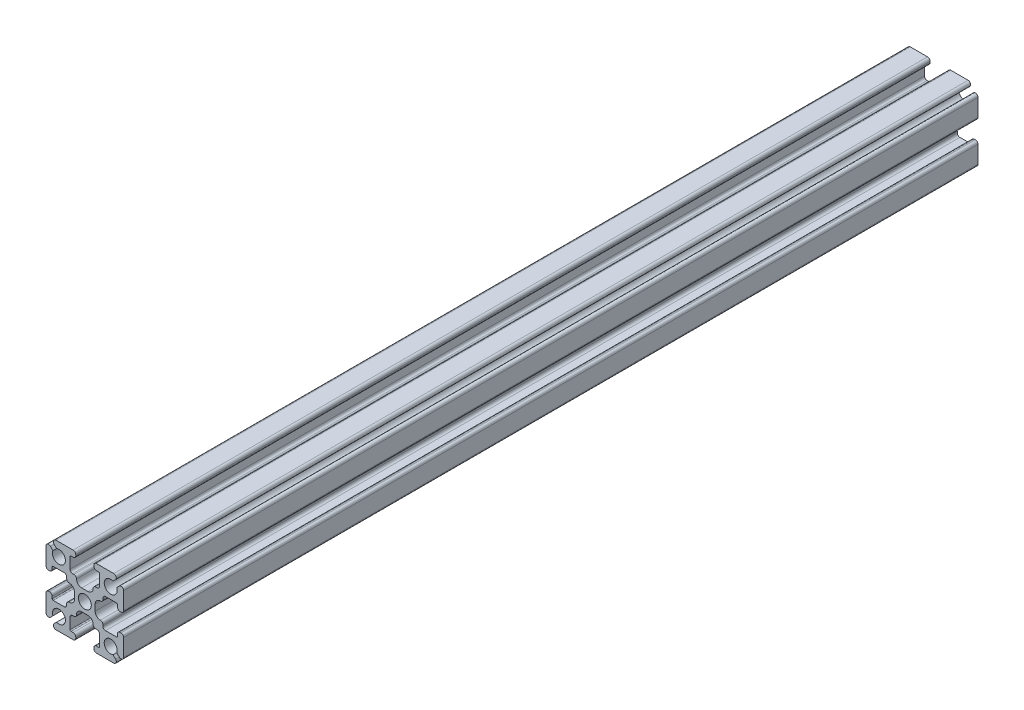
SolidWorks part; units mm, degrees
ref_plane "Front Plane" through (0, 0, 0) normal (0, 0, 1) x (1, 0, 0)
ref_plane "Top Plane" through (0, 0, 0) normal (0, 1, 0) x (1, 0, 0)
ref_plane "Right Plane" through (0, 0, 0) normal (1, 0, 0) x (0, 0, -1)
sketch "Sketch1" plane through (0, 0, 0) normal (0, 0, 1) x (1, 0, 0)
  line L0 (6.6464, 5.9393) -> (6.1636, 5.4565)
  line L1 (5.4565, 6.1636) -> (5.9393, 6.6464)
  line L2 (5.5858, 7.5) -> (2.25, 7.5)
  line L3 (1.75, 7) -> (1.75, 6.8)
  line L4 (2.25, 6.3) -> (2.65, 6.3)
  line L5 (2.85, 6.1) -> (2.85, 4)
  line L6 (2.35, 3.5) -> (2.1, 3.5)
  line L7 (0.6, 2) -> (-0.6, 2)
  line L8 (-2.1, 3.5) -> (-2.35, 3.5)
  line L9 (-2.85, 4) -> (-2.85, 6.1)
  line L10 (-2.65, 6.3) -> (-2.25, 6.3)
  line L11 (-1.75, 6.8) -> (-1.75, 7)
  line L12 (-2.25, 7.5) -> (-5.5858, 7.5)
  line L13 (-5.9393, 6.6464) -> (-5.4565, 6.1636)
  line L14 (-6.1636, 5.4565) -> (-6.6464, 5.9393)
  line L15 (-7.5, 5.5858) -> (-7.5, 2.25)
  line L16 (-7, 1.75) -> (-6.8, 1.75)
  line L17 (-6.3, 2.25) -> (-6.3, 2.65)
  line L18 (-6.1, 2.85) -> (-4, 2.85)
  line L19 (-3.5, 2.35) -> (-3.5, 2.1)
  line L20 (-2, 0.6) -> (-2, -0.6)
  line L21 (-3.5, -2.1) -> (-3.5, -2.35)
  line L22 (-4, -2.85) -> (-6.1, -2.85)
  line L23 (-6.3, -2.65) -> (-6.3, -2.25)
  line L24 (-6.8, -1.75) -> (-7, -1.75)
  line L25 (-7.5, -2.25) -> (-7.5, -5.5858)
  line L26 (-6.6464, -5.9393) -> (-6.1636, -5.4565)
  line L27 (-5.4565, -6.1636) -> (-5.9393, -6.6464)
  line L28 (-5.5858, -7.5) -> (-2.25, -7.5)
  line L29 (-1.75, -7) -> (-1.75, -6.8)
  line L30 (-2.25, -6.3) -> (-2.65, -6.3)
  line L31 (-2.85, -6.1) -> (-2.85, -4)
  line L32 (-2.35, -3.5) -> (-2.1, -3.5)
  line L33 (-0.6, -2) -> (0.6, -2)
  line L34 (2.1, -3.5) -> (2.35, -3.5)
  line L35 (2.85, -4) -> (2.85, -6.1)
  line L36 (2.65, -6.3) -> (2.25, -6.3)
  line L37 (1.75, -6.8) -> (1.75, -7)
  line L38 (2.25, -7.5) -> (5.5858, -7.5)
  line L39 (5.9393, -6.6464) -> (5.4565, -6.1636)
  line L40 (6.1636, -5.4565) -> (6.6464, -5.9393)
  line L41 (7.5, -5.5858) -> (7.5, -2.25)
  line L42 (7, -1.75) -> (6.8, -1.75)
  line L43 (6.3, -2.25) -> (6.3, -2.65)
  line L44 (6.1, -2.85) -> (4, -2.85)
  line L45 (3.5, -2.35) -> (3.5, -2.1)
  line L46 (2, -0.6) -> (2, 0.6)
  line L47 (3.5, 2.1) -> (3.5, 2.35)
  line L48 (4, 2.85) -> (6.1, 2.85)
  line L49 (6.3, 2.65) -> (6.3, 2.25)
  line L50 (6.8, 1.75) -> (7, 1.75)
  line L51 (7.5, 2.25) -> (7.5, 5.5858)
  circle A0 centre (0, 0) radius 1.25
  arc A1 (6.1636, 5.4565) -> (5.4565, 6.1636) centre (5, 5) cw
  arc A2 (5.9393, 6.6464) -> (5.5858, 7.5) centre (5.5858, 7) ccw
  arc A3 (2.25, 7.5) -> (1.75, 7) centre (2.25, 7) ccw
  arc A4 (1.75, 6.8) -> (2.25, 6.3) centre (2.25, 6.8) ccw
  arc A5 (2.65, 6.3) -> (2.85, 6.1) centre (2.65, 6.1) cw
  arc A6 (2.85, 4) -> (2.35, 3.5) centre (2.35, 4) cw
  arc A7 (2.1, 3.5) -> (1.6, 3) centre (2.1, 3) ccw
  arc A8 (1.6, 3) -> (0.6, 2) centre (0.6, 3) cw
  arc A9 (-0.6, 2) -> (-1.6, 3) centre (-0.6, 3) cw
  arc A10 (-1.6, 3) -> (-2.1, 3.5) centre (-2.1, 3) ccw
  arc A11 (-2.35, 3.5) -> (-2.85, 4) centre (-2.35, 4) cw
  arc A12 (-2.85, 6.1) -> (-2.65, 6.3) centre (-2.65, 6.1) cw
  arc A13 (-2.25, 6.3) -> (-1.75, 6.8) centre (-2.25, 6.8) ccw
  arc A14 (-1.75, 7) -> (-2.25, 7.5) centre (-2.25, 7) ccw
  arc A15 (-5.5858, 7.5) -> (-5.9393, 6.6464) centre (-5.5858, 7) ccw
  arc A16 (-5.4565, 6.1636) -> (-6.1636, 5.4565) centre (-5, 5) cw
  arc A17 (-6.6464, 5.9393) -> (-7.5, 5.5858) centre (-7, 5.5858) ccw
  arc A18 (-7.5, 2.25) -> (-7, 1.75) centre (-7, 2.25) ccw
  arc A19 (-6.8, 1.75) -> (-6.3, 2.25) centre (-6.8, 2.25) ccw
  arc A20 (-6.3, 2.65) -> (-6.1, 2.85) centre (-6.1, 2.65) cw
  arc A21 (-4, 2.85) -> (-3.5, 2.35) centre (-4, 2.35) cw
  arc A22 (-3.5, 2.1) -> (-3, 1.6) centre (-3, 2.1) ccw
  arc A23 (-3, 1.6) -> (-2, 0.6) centre (-3, 0.6) cw
  arc A24 (-2, -0.6) -> (-3, -1.6) centre (-3, -0.6) cw
  arc A25 (-3, -1.6) -> (-3.5, -2.1) centre (-3, -2.1) ccw
  arc A26 (-3.5, -2.35) -> (-4, -2.85) centre (-4, -2.35) cw
  arc A27 (-6.1, -2.85) -> (-6.3, -2.65) centre (-6.1, -2.65) cw
  arc A28 (-6.3, -2.25) -> (-6.8, -1.75) centre (-6.8, -2.25) ccw
  arc A29 (-7, -1.75) -> (-7.5, -2.25) centre (-7, -2.25) ccw
  arc A30 (-7.5, -5.5858) -> (-6.6464, -5.9393) centre (-7, -5.5858) ccw
  arc A31 (-6.1636, -5.4565) -> (-5.4565, -6.1636) centre (-5, -5) cw
  arc A32 (-5.9393, -6.6464) -> (-5.5858, -7.5) centre (-5.5858, -7) ccw
  arc A33 (-2.25, -7.5) -> (-1.75, -7) centre (-2.25, -7) ccw
  arc A34 (-1.75, -6.8) -> (-2.25, -6.3) centre (-2.25, -6.8) ccw
  arc A35 (-2.65, -6.3) -> (-2.85, -6.1) centre (-2.65, -6.1) cw
  arc A36 (-2.85, -4) -> (-2.35, -3.5) centre (-2.35, -4) cw
  arc A37 (-2.1, -3.5) -> (-1.6, -3) centre (-2.1, -3) ccw
  arc A38 (-1.6, -3) -> (-0.6, -2) centre (-0.6, -3) cw
  arc A39 (0.6, -2) -> (1.6, -3) centre (0.6, -3) cw
  arc A40 (1.6, -3) -> (2.1, -3.5) centre (2.1, -3) ccw
  arc A41 (2.35, -3.5) -> (2.85, -4) centre (2.35, -4) cw
  arc A42 (2.85, -6.1) -> (2.65, -6.3) centre (2.65, -6.1) cw
  arc A43 (2.25, -6.3) -> (1.75, -6.8) centre (2.25, -6.8) ccw
  arc A44 (1.75, -7) -> (2.25, -7.5) centre (2.25, -7) ccw
  arc A45 (5.5858, -7.5) -> (5.9393, -6.6464) centre (5.5858, -7) ccw
  arc A46 (5.4565, -6.1636) -> (6.1636, -5.4565) centre (5, -5) cw
  arc A47 (6.6464, -5.9393) -> (7.5, -5.5858) centre (7, -5.5858) ccw
  arc A48 (7.5, -2.25) -> (7, -1.75) centre (7, -2.25) ccw
  arc A49 (6.8, -1.75) -> (6.3, -2.25) centre (6.8, -2.25) ccw
  arc A50 (6.3, -2.65) -> (6.1, -2.85) centre (6.1, -2.65) cw
  arc A51 (4, -2.85) -> (3.5, -2.35) centre (4, -2.35) cw
  arc A52 (3.5, -2.1) -> (3, -1.6) centre (3, -2.1) ccw
  arc A53 (3, -1.6) -> (2, -0.6) centre (3, -0.6) cw
  arc A54 (2, 0.6) -> (3, 1.6) centre (3, 0.6) cw
  arc A55 (3, 1.6) -> (3.5, 2.1) centre (3, 2.1) ccw
  arc A56 (3.5, 2.35) -> (4, 2.85) centre (4, 2.35) cw
  arc A57 (6.1, 2.85) -> (6.3, 2.65) centre (6.1, 2.65) cw
  arc A58 (6.3, 2.25) -> (6.8, 1.75) centre (6.8, 2.25) ccw
  arc A59 (7, 1.75) -> (7.5, 2.25) centre (7, 2.25) ccw
  arc A60 (7.5, 5.5858) -> (6.6464, 5.9393) centre (7, 5.5858) ccw
extrude "Boss-Extrude1" add sketch "Sketch1" along normal blind 165.1
